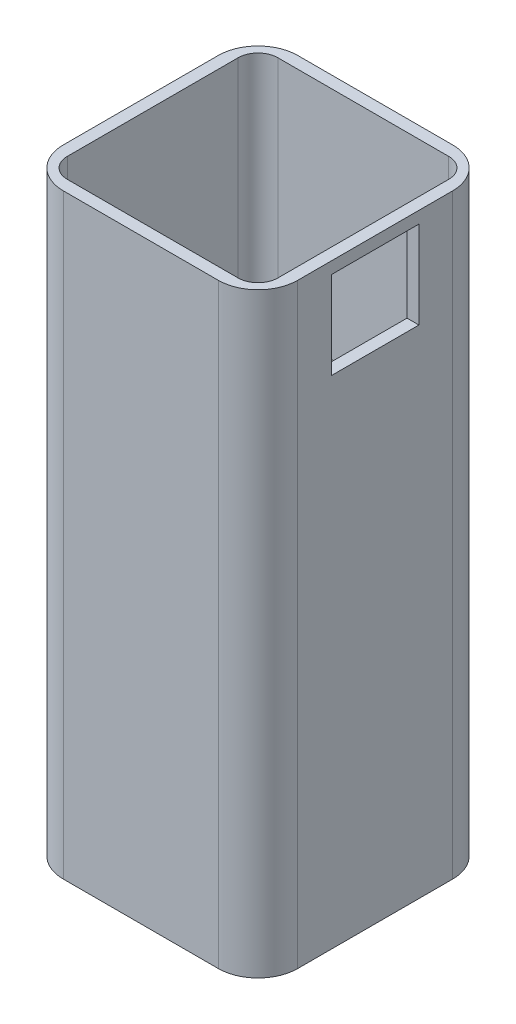
SolidWorks part; units mm, degrees
ref_plane "Front Plane" through (0, 0, 0) normal (0, 0, 1) x (1, 0, 0)
ref_plane "Top Plane" through (0, 0, 0) normal (0, 1, 0) x (1, 0, 0)
ref_plane "Right Plane" through (0, 0, 0) normal (1, 0, 0) x (0, 0, -1)
sketch "Sketch1" plane through (0, 0, 0) normal (0, 1, 0) x (1, 0, 0)
  line L1 (-29.5, -29.5) -> (29.5, -29.5)
  line L2 (-29.5, -29.5) -> (-29.5, 29.5)
  line L3 (-29.5, 29.5) -> (29.5, 29.5)
  line L4 (29.5, -29.5) -> (29.5, 29.5)
  line L5 (-29.5, -29.5) -> (29.5, 29.5) construction
  line L6 (-29.5, 29.5) -> (29.5, -29.5) construction
  line L7 (-26.5, -26.5) -> (26.5, -26.5)
  line L8 (-26.5, -26.5) -> (-26.5, 26.5)
  line L9 (-26.5, 26.5) -> (26.5, 26.5)
  line L10 (26.5, -26.5) -> (26.5, 26.5)
  line L11 (-26.5, -26.5) -> (26.5, 26.5) construction
  line L12 (-26.5, 26.5) -> (26.5, -26.5) construction
  point P0 (0, 0)
  point P6 (0, 0)
  dimension "D1" = 3
  dimension "D2" = 3
  dimension "D3" = 53
  dimension "D4" = 53
extrude "Boss-Extrude1" add sketch "Sketch1" along normal blind 150
fillet "Fillet1" radius 10 4 edges at (29.5, 75, -29.5) (29.5, 75, 29.5) (-29.5, 75, 29.5) (-29.5, 75, -29.5)
fillet "Fillet2" radius 5 4 edges at (-26.5, 75, -26.5) (-26.5, 75, 26.5) (26.5, 75, 26.5) (26.5, 75, -26.5)
sketch "Sketch3" plane through (0, 0, -29.5) normal (0, 0, -1) x (-1, 0, 0)
  line L23 (0, 32.45) -> (0, -32.45) construction
  line L24 (-11, 69) -> (11, 69)
  line L25 (-11, 69) -> (-11, 91)
  line L26 (-11, 91) -> (11, 91)
  line L27 (11, 69) -> (11, 91)
  line L28 (-11, 69) -> (11, 91) construction
  line L29 (-11, 91) -> (11, 69) construction
  line L30 (32.45, 0) -> (-32.45, 0) construction
  point P0 (0, 80)
  dimension "D1" = 22
  dimension "D2" = 22
  dimension "D3" = 80
extrude "Cut-Extrude2" cut sketch "Sketch3" against normal blind 3
sketch "Sketch5" plane through (29.5, 0, 0) normal (1, 0, 0) x (0, 0, -1)
  line L0 (0, 32.45) -> (0, -32.45) construction
  line L1 (-11, 125) -> (11, 125)
  line L2 (-11, 125) -> (-11, 147)
  line L3 (-11, 147) -> (11, 147)
  line L4 (11, 125) -> (11, 147)
  line L5 (-11, 125) -> (11, 147) construction
  line L6 (-11, 147) -> (11, 125) construction
  line L7 (-19.5, 150) -> (19.5, 150) construction
  point P0 (0, 136)
  dimension "D1" = 3
  dimension "D2" = 22
  dimension "D3" = 22
extrude "Cut-Extrude4" cut sketch "Sketch5" against normal up to next
